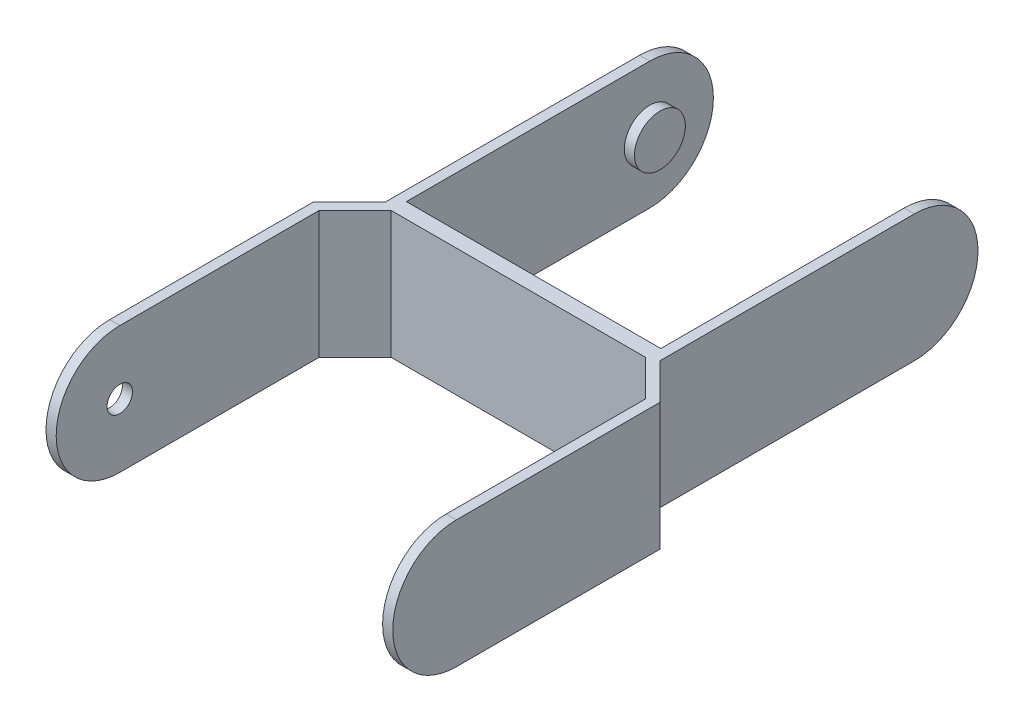
SolidWorks part; units mm, degrees
material "Plastique personnalisé"
ref_plane "Plan de face" through (0, 0, 0) normal (0, 0, 1) x (1, 0, 0)
ref_plane "Plan de dessus" through (0, 0, 0) normal (0, 1, 0) x (1, 0, 0)
ref_plane "Plan de droite" through (0, 0, 0) normal (1, 0, 0) x (0, 0, -1)
sketch "Esquisse1" plane through (0, 0, 0) normal (0, 1, 0) x (1, 0, 0)
  line L1 (-34.0711, -59.1028) -> (-34.0711, -19.1028)
  line L2 (-34.0711, -19.1028) -> (-27, -12.0317)
  line L3 (-27, -12.0317) -> (-27, 37.9683)
  line L4 (-27, 37.9683) -> (-25, 37.9683)
  line L5 (-25, 37.9683) -> (-25, -9.8602)
  line L6 (-25, -12.8602) -> (-32.0711, -19.9312)
  line L7 (-32.0711, -19.9312) -> (-32.0711, -59.1028)
  line L8 (-32.0711, -59.1028) -> (-34.0711, -59.1028)
  line L9 (32.0711, -59.1028) -> (34.0711, -59.1028)
  line L10 (-25, -12.8602) -> (25, -12.8602)
  line L12 (-25, -9.8602) -> (25, -9.8602)
  line L14 (32.0711, -19.9312) -> (32.0711, -59.1028)
  line L15 (25, -12.8602) -> (32.0711, -19.9312)
  line L16 (25, 37.9683) -> (25, -9.8602)
  line L17 (27, 37.9683) -> (25, 37.9683)
  line L18 (27, -12.0317) -> (27, 37.9683)
  line L19 (34.0711, -19.1028) -> (27, -12.0317)
  line L20 (34.0711, -59.1028) -> (34.0711, -19.1028)
  dimension "D1" = 135
  dimension "D2" = 40
  dimension "D3" = 10
  dimension "D4" = 2
  dimension "D5" = 2
  dimension "D6" = 2
  dimension "D7" = 135
  dimension "D8" = 50
  dimension "D10" = 3
extrude "Boss.-Extru.1" add sketch "Esquisse1" along normal blind 25 contours L12 L16 L17 L18 L19 L20 L9 L14 L15 L10 L6 L7 L8 L1 L2 L3 L4 L5
ref_plane "Plan1" through (34.0711, 0, 0) normal (1, 0, 0) x (0, 0, -1)
sketch "Esquisse2" plane through (34.0711, 0, 0) normal (1, 0, 0) x (0, 0, -1)
  line L4 (-59.1028, 0) -> (-19.1028, 0)
  line L5 (-19.1028, 0) -> (-19.1028, 25)
  line L6 (-19.1028, 25) -> (-59.1028, 25)
  line L7 (-59.1028, 25) -> (-59.1028, 0)
  line L8 (-59.1028, 0) -> (-19.1028, 0)
  line L9 (-19.1028, 0) -> (-19.1028, 25)
  line L10 (-19.1028, 25) -> (-59.1028, 25)
  arc A0 (-59.1028, 0) -> (-59.1028, 25) centre (-59.1028, 12.5) cw
  dimension "D1" = 0
extrude "Boss.-Extru.2" add sketch "Esquisse2" against normal blind 2 contours A0 L10 L9 L8
ref_plane "Plan2" through (27, 0, 0) normal (1, 0, 0) x (0, 0, -1)
sketch "Esquisse3" plane through (27, 0, 0) normal (1, 0, 0) x (0, 0, -1)
  line L0 (37.9683, 25) -> (37.9683, 0) construction
  line L1 (37.9683, 25) -> (37.9683, 0)
  arc A0 (37.9683, 0) -> (37.9683, 25) centre (37.9683, 12.5) ccw
extrude "Boss.-Extru.3" add sketch "Esquisse3" against normal blind 2
ref_plane "Plan3" through (-34.0711, 0, 0) normal (-1, 0, 0) x (0, 0, 1)
sketch "Esquisse4" plane through (-34.0711, 0, 0) normal (-1, 0, 0) x (0, 0, 1)
  line L0 (59.1028, 25) -> (59.1028, 0) construction
  line L1 (59.1028, 24.5046) -> (59.1028, 0)
  line L2 (59.1028, 25) -> (59.1028, 0)
  arc A0 (59.1028, 0) -> (59.1028, 25) centre (59.1028, 12.5) ccw
extrude "Boss.-Extru.4" add sketch "Esquisse4" against normal blind 2 contours A0 L2
ref_plane "Plan4" through (-27, 0, 0) normal (-1, 0, 0) x (0, 0, 1)
sketch "Esquisse5" plane through (-27, 0, 0) normal (-1, 0, 0) x (0, 0, 1)
  line L0 (-37.9683, 25) -> (-37.9683, 0) construction
  line L1 (-37.9683, 0) -> (-37.9683, 25)
  arc A0 (-37.9683, 25) -> (-37.9683, 0) centre (-37.9683, 12.5) ccw
extrude "Boss.-Extru.5" add sketch "Esquisse5" against normal blind 2 contours A0 L1
sketch "Esquisse6" plane through (-34.0711, 0, 0) normal (-1, 0, 0) x (0, 0, 1)
  circle A0 centre (59.1028, 12.5) radius 2.5
  dimension "D1" = 5
extrude "Enlèv. mat.-Extru.1" cut sketch "Esquisse6" against normal blind 10
ref_plane "Plan5" through (-25, 0, 0) normal (1, 0, 0) x (0, 0, -1)
sketch "Esquisse7" plane through (-25, 0, 0) normal (1, 0, 0) x (0, 0, -1)
  circle A0 centre (37.9683, 12.5) radius 5
  arc A1 (37.9683, 0) -> (37.9683, 25) centre (37.9683, 12.5) ccw construction
  dimension "D2" = 10
  dimension "D1" = 0
extrude "Boss.-Extru.6" add sketch "Esquisse7" along normal blind 2
ref_plane "Plan6" through (-23, 0, 0) normal (1, 0, 0) x (0, 0, -1)
sketch "Esquisse8" plane through (-23, 0, 0) normal (1, 0, 0) x (0, 0, -1)
  circle A0 centre (37.9683, 12.5) radius 2.5
ref_plane "Plan8" through (25, 0, 0) normal (-1, 0, 0) x (0, 0, 1)
sketch "Esquisse9" plane through (25, 0, 0) normal (-1, 0, 0) x (0, 0, 1)
  circle A0 centre (-39.4335, 13.1509) radius 5
extrude "Boss.-Extru.8" add sketch "Esquisse9" along normal blind 2 contours A0
ref_plane "Plan9" through (23, 0, 0) normal (-1, 0, 0) x (0, 0, 1)
sketch "Esquisse10" plane through (23, 0, 0) normal (-1, 0, 0) x (0, 0, 1)
  circle A0 centre (-39.4335, 13.1509) radius 2.5
  circle A1 centre (-39.4335, 13.1509) radius 5 construction
  dimension "D1" = 0
extrude "Boss.-Extru.9" add sketch "Esquisse10" along normal blind 2 contours A0
